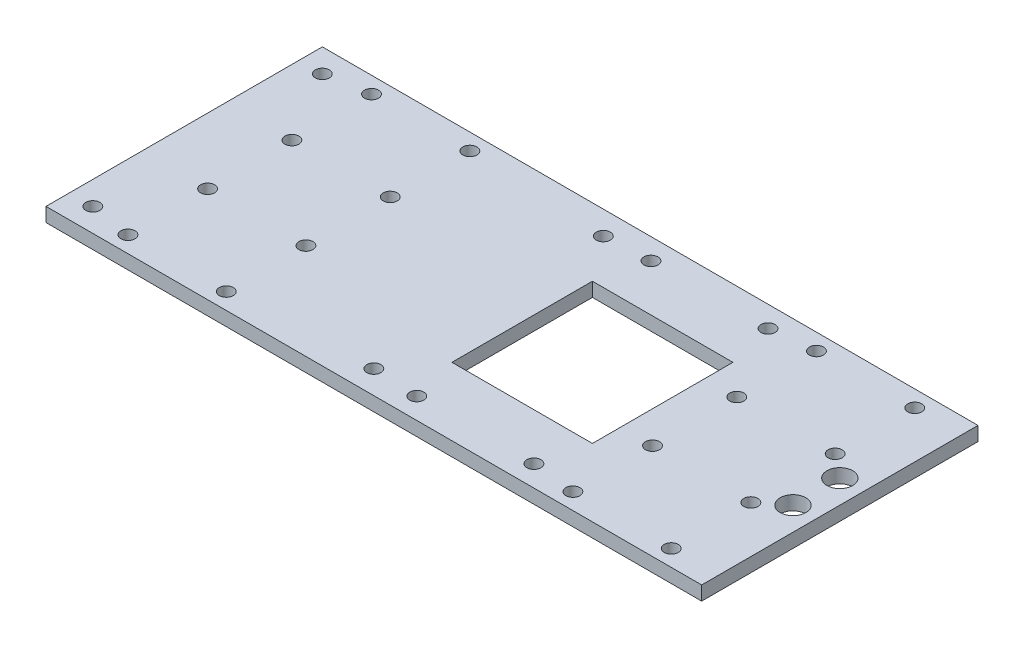
SolidWorks part; units mm, degrees
ref_plane "Front Plane" through (0, 0, 0) normal (0, 0, 1) x (1, 0, 0)
ref_plane "Top Plane" through (0, 0, 0) normal (0, 1, 0) x (1, 0, 0)
ref_plane "Right Plane" through (0, 0, 0) normal (1, 0, 0) x (0, 0, -1)
sketch "Sketch1" plane through (0, 0, 0) normal (0, 1, 0) x (1, 0, 0)
  line L0 (-5, 24.5) -> (-5, -24.5) construction
  line L1 (-70, -29.5) -> (70, -29.5)
  line L2 (-70, -29.5) -> (-70, 29.5)
  line L3 (-70, 29.5) -> (70, 29.5)
  line L4 (70, -29.5) -> (70, 29.5)
  line L5 (-70, -29.5) -> (70, 29.5) construction
  line L6 (-70, 29.5) -> (70, -29.5) construction
  line L7 (-56, 26) -> (-35, 26) construction
  line L8 (-56, 26) -> (-56, 9) construction
  line L9 (-56, 9) -> (-35, 9) construction
  line L10 (-35, 26) -> (-35, 9) construction
  line L11 (39, 26) -> (60, 26) construction
  line L12 (39, 26) -> (39, 9) construction
  line L13 (39, 9) -> (60, 9) construction
  line L14 (60, 26) -> (60, 9) construction
  line L15 (39, -9) -> (60, -9) construction
  line L16 (39, -9) -> (39, -26) construction
  line L17 (39, -26) -> (60, -26) construction
  line L18 (60, -9) -> (60, -26) construction
  line L19 (-56, -9) -> (-35, -9) construction
  line L20 (-56, -9) -> (-56, -26) construction
  line L21 (-56, -26) -> (-35, -26) construction
  line L22 (-35, -9) -> (-35, -26) construction
  line L23 (39, 9) -> (39, -9) construction
  line L24 (-5, -24.5) -> (-65, -24.5) construction
  line L25 (-65, -24.5) -> (-65, 24.5) construction
  line L26 (-65, 24.5) -> (-5, 24.5) construction
  line L28 (29.6714, 25) -> (4.6714, 25) construction
  line L29 (29.6714, 25) -> (29.6714, -25) construction
  line L30 (29.6714, -25) -> (4.6714, -25) construction
  line L31 (4.6714, 25) -> (4.6714, -25) construction
  line L32 (2.1714, -15) -> (32.1714, -15)
  line L33 (2.1714, -15) -> (2.1714, 15)
  line L34 (2.1714, 15) -> (32.1714, 15)
  line L35 (32.1714, -15) -> (32.1714, 15)
  line L36 (2.1714, -15) -> (32.1714, 15) construction
  line L37 (2.1714, 15) -> (32.1714, -15) construction
  circle A0 centre (-35, 26) radius 1.5
  circle A1 centre (-56, 26) radius 1.5
  circle A2 centre (-56, 9) radius 1.5
  circle A3 centre (-35, 9) radius 1.5
  circle A4 centre (-35, -9) radius 1.5
  circle A5 centre (-56, -9) radius 1.5
  circle A6 centre (-35, -26) radius 1.5
  circle A7 centre (-56, -26) radius 1.5
  circle A8 centre (60, 26) radius 1.5
  circle A9 centre (39, 26) radius 1.5
  circle A10 centre (39, -9) radius 1.5
  circle A11 centre (60, -9) radius 1.5
  circle A12 centre (60, -26) radius 1.5
  circle A13 centre (39, -26) radius 1.5
  circle A14 centre (60, 9) radius 1.5
  circle A15 centre (39, 9) radius 1.5
  circle A20 centre (-5, -24.5) radius 1.5
  circle A21 centre (-5, 24.5) radius 1.5
  circle A22 centre (-65, 24.5) radius 1.5
  circle A23 centre (-65, -24.5) radius 1.5
  circle A24 centre (29.6714, 25) radius 1.5
  circle A25 centre (29.6714, -25) radius 1.5
  circle A26 centre (4.6714, -25) radius 1.5
  circle A27 centre (4.6714, 25) radius 1.5
  point P0 (0, 0)
  point P36 (39, 0)
  point P47 (70, 0)
  point P48 (-5, 0)
  point P57 (29.6714, 0)
  point P58 (17.1714, 0)
  point P63 (0, 0)
  point P64 (17.1714, 25)
  point P65 (0, 0)
  dimension "D5" = 3
  dimension "D9" = 3
  dimension "D15" = 3
  dimension "D1" = 95
  dimension "D2" = 35
  dimension "D3" = 21
  dimension "D4" = 17
  dimension "D6" = 59
  dimension "D7" = 10
  dimension "D8" = 140
  dimension "D10" = 5
  dimension "D11" = 5
  dimension "D12" = 60
  dimension "D13" = 50
  dimension "D14" = 25
  dimension "D16" = 40.3286
  dimension "D17" = 30
  dimension "D18" = 30
extrude "Boss-Extrude1" add sketch "Sketch1" along normal blind 3
sketch "Sketch8" plane through (0, 3, 0) normal (0, 1, 0) x (1, 0, 0)
  line L0 (70, -29.5) -> (70, 29.5) construction
  line L1 (65, 5) -> (65, -5) construction
  circle A0 centre (65, 5) radius 2.75
  circle A1 centre (65, -5) radius 2.75
  point P6 (70, 0)
  point P7 (65, 0)
  dimension "D1" = 5.5
  dimension "D2" = 10
  dimension "D3" = 5
extrude "Cut-Extrude6" cut sketch "Sketch8" against normal through all
